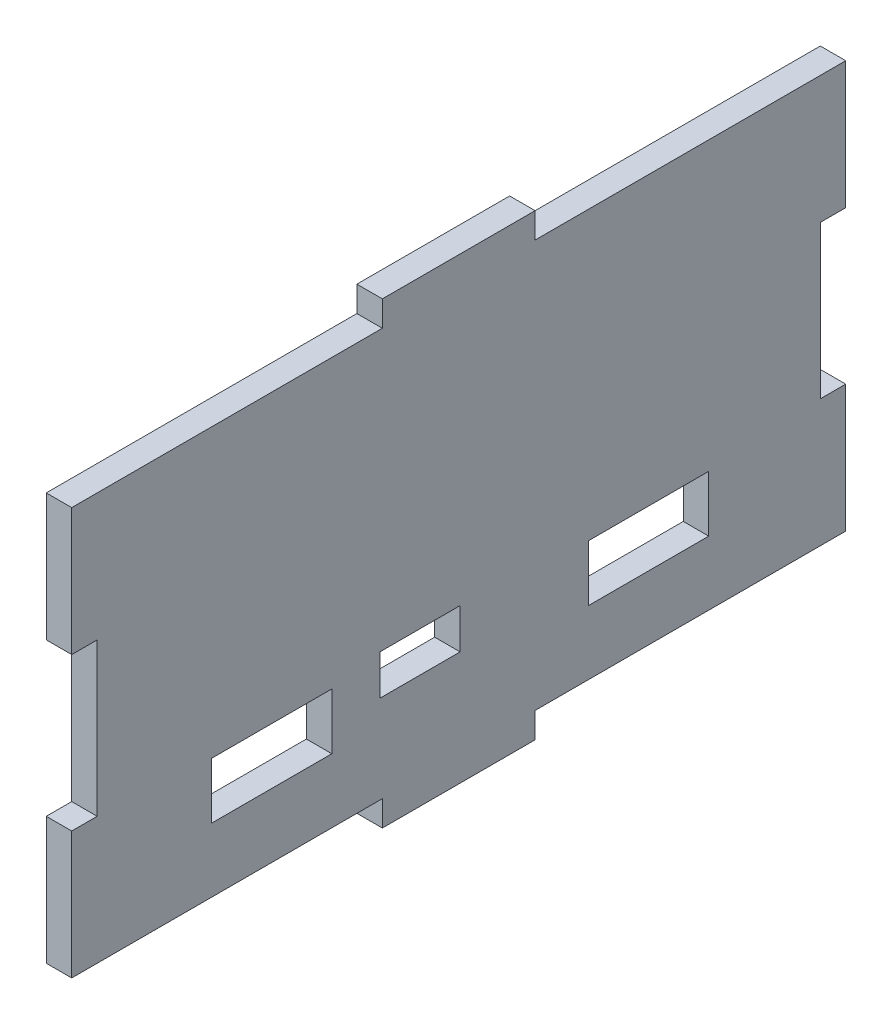
SolidWorks part; units mm, degrees
ref_plane "Front Plane" through (0, 0, 0) normal (0, 0, 1) x (1, 0, 0)
ref_plane "Top Plane" through (0, 0, 0) normal (0, 1, 0) x (1, 0, 0)
ref_plane "Right Plane" through (0, 0, 0) normal (1, 0, 0) x (0, 0, -1)
sketch "Sketch1" plane through (0, 0, 0) normal (1, 0, 0) x (0, 0, -1)
  line L0 (48.26, 50.8) -> (48.26, -7.345) construction
  line L1 (0, 0) -> (38.735, 0)
  line L2 (0, 0) -> (0, 15.875)
  line L3 (0, 50.8) -> (38.735, 50.8)
  line L4 (96.52, 0) -> (96.52, 15.875)
  line L5 (38.735, 50.8) -> (38.735, 53.975)
  line L6 (38.735, 53.975) -> (57.785, 53.975)
  line L7 (57.785, 53.975) -> (57.785, 50.8)
  line L8 (48.26, 53.975) -> (48.26, 50.8) construction
  line L9 (96.52, 25.4) -> (-8.8493, 25.4) construction
  line L10 (0, 34.925) -> (3.175, 34.925)
  line L11 (3.175, 34.925) -> (3.175, 15.875)
  line L12 (3.175, 15.875) -> (0, 15.875)
  line L13 (0, 34.925) -> (0, 50.8)
  line L14 (57.785, 50.8) -> (96.52, 50.8)
  line L15 (93.345, 15.875) -> (96.52, 15.875)
  line L16 (93.345, 34.925) -> (93.345, 15.875)
  line L17 (96.52, 34.925) -> (93.345, 34.925)
  line L18 (57.785, -3.175) -> (57.785, 0)
  line L19 (38.735, 0) -> (38.735, -3.175)
  line L20 (38.735, -3.175) -> (57.785, -3.175)
  line L21 (96.52, 34.925) -> (96.52, 50.8)
  line L22 (57.785, 0) -> (96.52, 0)
  line L23 (17.4354, 0) -> (17.4354, 8) construction
  line L24 (17.4354, 8) -> (17.4354, 15)
  line L25 (17.4354, 15) -> (32.4354, 15)
  line L26 (32.4354, 15) -> (32.4354, 8)
  line L27 (32.4354, 8) -> (17.4354, 8)
  line L28 (38.4354, 0) -> (38.4354, 11) construction
  line L29 (64.4354, 0) -> (64.4354, 8) construction
  line L30 (38.4354, 11) -> (48.4354, 11)
  line L31 (38.4354, 11) -> (38.4354, 16)
  line L32 (38.4354, 16) -> (48.4354, 16)
  line L33 (48.4354, 11) -> (48.4354, 16)
  line L35 (64.4354, 8) -> (79.4354, 8)
  line L36 (64.4354, 8) -> (64.4354, 15)
  line L37 (64.4354, 15) -> (79.4354, 15)
  line L38 (79.4354, 8) -> (79.4354, 15)
  line L39 (48.26, 4) -> (48.26, -3.175) construction
  point P17 (3.175, 25.4)
  point P46 (0, 0)
  point P47 (0, 0)
  point P48 (73.76, 4)
  point P49 (83.9936, 4)
  point P50 (0, 0)
  point P51 (0, 0)
  dimension "D1" = 50.8
  dimension "D2" = 96.52
  dimension "D3" = 19.05
  dimension "D4" = 3.175
  dimension "D5" = 3.175
  dimension "D6" = 19.05
  dimension "D7" = 8
  dimension "D8" = 7
  dimension "D9" = 15
  dimension "D10" = 11
  dimension "D11" = 5
  dimension "D12" = 6
  dimension "D13" = 10
  dimension "D14" = 8
  dimension "D15" = 16
  dimension "D16" = 15
  dimension "D17" = 7
extrude "Boss-Extrude1" add sketch "Sketch1" along normal blind 3.175
